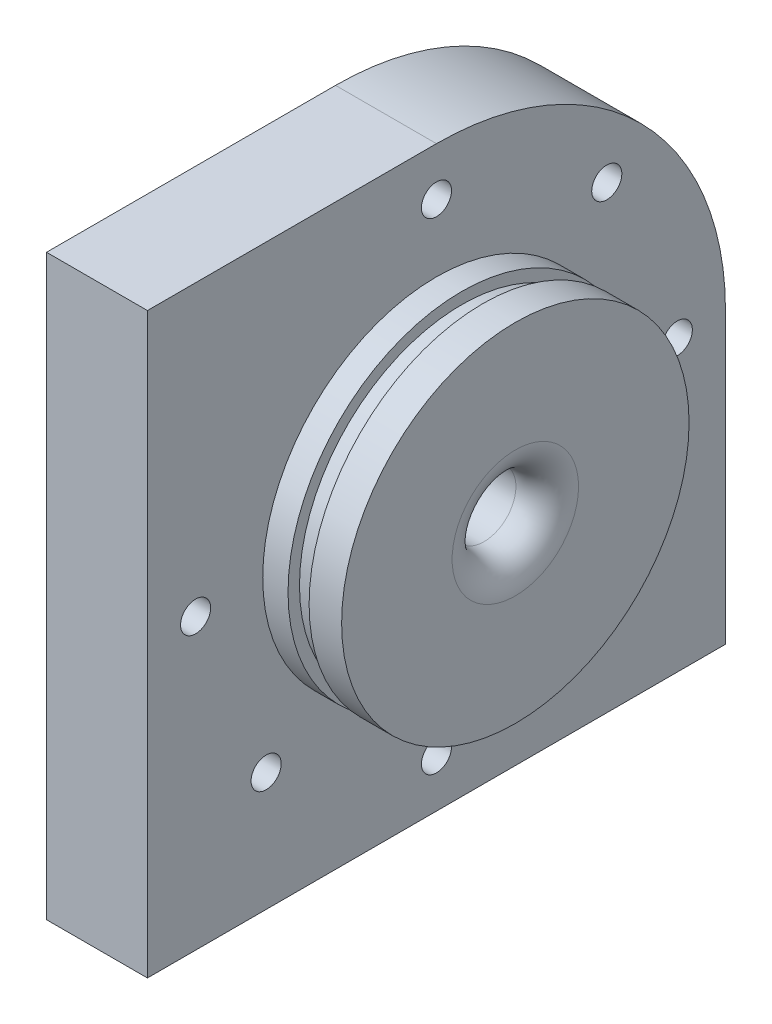
SolidWorks part; units mm, degrees
material "6061 Alloy"
ref_plane "Front Plane" through (0, 0, 0) normal (0, 0, 1) x (1, 0, 0)
ref_plane "Top Plane" through (0, 0, 0) normal (0, 1, 0) x (1, 0, 0)
ref_plane "Right Plane" through (0, 0, 0) normal (1, 0, 0) x (0, 0, -1)
sketch "Sketch1" plane through (0, 0, 0) normal (1, 0, 0) x (0, 0, -1)
  circle A0 centre (0, 0) radius 36.6395
  dimension "D1" = 73.279
extrude "Housing Fitting Extrude" add sketch "Sketch1" along normal blind 16.637
sketch "Sketch2" plane through (0, 0, 0) normal (-1, 0, 0) x (0, 0, 1)
  line L0 (60.96, 0) -> (60.96, 60.96)
  line L1 (60.96, 60.96) -> (0, 60.96)
  line L2 (60.96, 0) -> (60.96, -54.61)
  line L3 (60.96, -60.96) -> (-60.96, -60.96)
  line L7 (0, -55) -> (0, 55) construction
  line L11 (-60.96, 0) -> (-60.96, -54.61)
  line L12 (60.96, -60.96) -> (60.96, -54.61)
  line L13 (-60.96, -60.96) -> (-60.96, -54.61)
  arc A0 (0, 60.96) -> (-60.96, 0) centre (0, 0) ccw
extrude "Housing Body 1" add sketch "Sketch2" along normal blind 21.2852 contours A0 L11 L13 L3 L12 L2 L0 L1
sketch "Sketch3" plane through (16.637, 0, 0) normal (1, 0, 0) x (0, 0, -1)
  circle A0 centre (0, 0) radius 6.731
extrude "Impeller Bore" cut sketch "Sketch3" against normal blind 17.018
sketch "Sketch4" plane through (-0.381, 0, 0) normal (1, 0, 0) x (0, 0, -1)
  circle A0 centre (0, 0) radius 4
extrude "Shaft Bore" cut sketch "Sketch4" against normal up to surface (20.9042 mm away) up to face at (-21.2852, 2.525, -2.525)
ref_plane "O-Ring Sketch Plane" through (8.509, 0, 0) normal (1, 0, 0) x (0, 0, -1)
sketch "Sketch5" plane through (8.509, 0, 0) normal (1, 0, 0) x (0, 0, -1)
  circle A0 centre (0, 0) radius 36.6395
  circle A1 centre (0, 0) radius 34.2265
  dimension "D1" = 73.279
  dimension "D2" = 68.453
extrude "O-Ring Cut" cut sketch "Sketch5" against normal blind 3.175 and the other way blind 1.27
sketch "Sketch12" plane through (0, 0, 0) normal (1, 0, 0) x (0, 0, -1)
  line L0 (-60.96, 60.96) -> (0, 60.96) construction
  circle A0 centre (-50.8, 0) radius 3.175
  circle A1 centre (0, 0) radius 6.731 construction
  dimension "D1" = 50.8
  dimension "D3" = 6.35
  dimension "D2" = 60.96
extrude "Cut-Extrude2" cut sketch "Sketch12" against normal up to surface (21.2852 mm away) up to face at (-21.2852, 0, 4)
pattern_circular "CirPattern1" count 8 over 360 about axis through (0, 0, 0) along (1, 0, 0) skipping 7 of "Cut-Extrude2"
sketch "Sketch14" plane through (0, -60.96, 0) normal (0, -1, 0) x (1, 0, 0)
  line L0 (-21.2852, 60.96) -> (-21.2852, -60.96) construction
  line L2 (-21.2852, 60.96) -> (0, 60.96) construction
  circle A0 centre (-8.128, -46.7543) radius 2.5797
  circle A1 centre (-8.128, 41.9141) radius 2.5797
  dimension "D1" = 5.1594
  dimension "D2" = 5.1594
  dimension "D3" = 88.6684
  dimension "D4" = 13.1572
  dimension "D5" = 13.1572
  dimension "D6" = 19.0459
extrude "Cut-Extrude4" cut sketch "Sketch14" against normal blind 16.51
sketch "Sketch15" plane through (0, 0, -60.96) normal (0, 0, -1) x (-1, 0, 0)
  line L0 (21.2852, 0) -> (21.2852, -60.96) construction
  line L1 (21.2852, -60.96) -> (0, -60.96) construction
  circle A0 centre (8.128, -39.3375) radius 2.5797
  dimension "D1" = 5.1594
  dimension "D2" = 13.1572
  dimension "D3" = 21.6225
extrude "Cut-Extrude5" cut sketch "Sketch15" against normal blind 10.922
fillet "Fillet1" radius 6.604 1 edges at (16.637, 0, -6.731)
sketch "Sketch17" plane through (-21.2852, 0, 0) normal (-1, 0, 0) x (0, 0, 1)
  circle A0 centre (0, 0) radius 17.5006
  dimension "D1" = 35.0012
extrude "Cut-Extrude8" cut sketch "Sketch17" against normal offset from surface (25.2222 mm away) 12.7 up to face at (16.637, 0, -13.335)
sketch "Sketch18" plane through (-21.2852, 0, 0) normal (-1, 0, 0) x (0, 0, 1)
  circle A0 centre (0, 0) radius 24.9174
  dimension "D1" = 49.8348
extrude "Cut-Extrude9" cut sketch "Sketch18" against normal offset from surface (15.3162 mm away) 9.906 up to face at (3.937, 0, -17.5006)
sketch "Sketch19" plane through (-21.2852, 0, 0) normal (-1, 0, 0) x (0, 0, 1)
  circle A0 centre (0, 0) radius 28.575 construction
  circle A1 centre (0, 28.575) radius 1.7272
  circle A2 centre (0, 0) radius 28.575 construction
  circle A3 centre (28.575, 0) radius 1.7272
  circle A4 centre (0, 0) radius 28.575 construction
  circle A5 centre (0, -28.575) radius 1.7272
  circle A6 centre (0, 0) radius 28.575 construction
  circle A7 centre (-28.575, 0) radius 1.7272
  point P17 (0, 0)
  dimension "D1" = 57.15
  dimension "D2" = 3.4544
  dimension "D3" = 4
extrude "Cut-Extrude10" cut sketch "Sketch19" against normal blind 9.525
equation "\"D1@Housing Body 1\"=1.563-0.67"
equation "\"D1\"= 0.2 + 0.3135 + 0.750"
